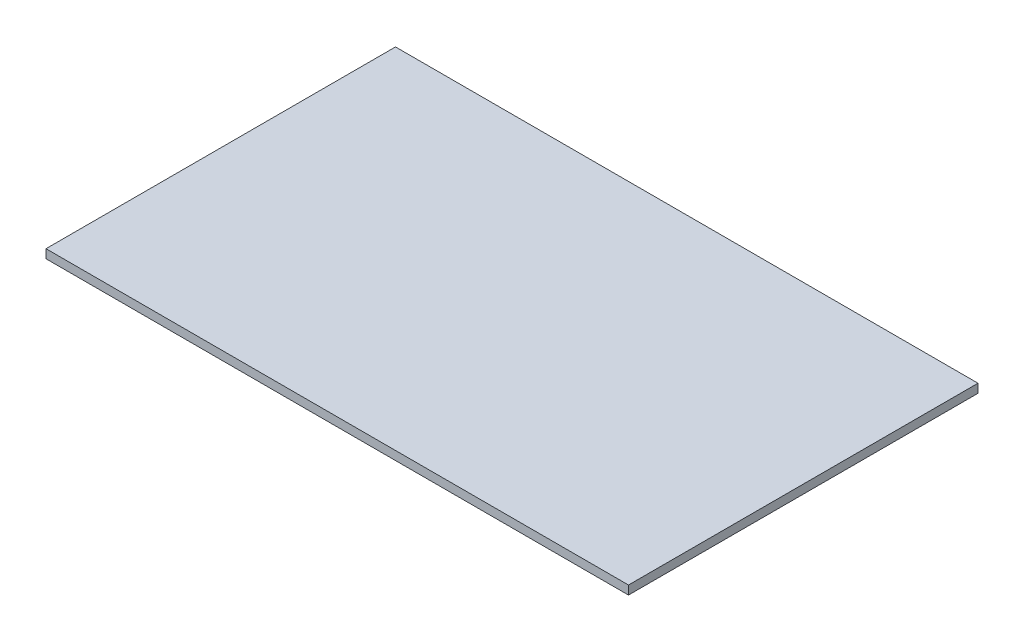
SolidWorks part; units mm, degrees
ref_plane "Front Plane" through (0, 0, 0) normal (0, 0, 1) x (1, 0, 0)
ref_plane "Top Plane" through (0, 0, 0) normal (0, 1, 0) x (1, 0, 0)
ref_plane "Right Plane" through (0, 0, 0) normal (1, 0, 0) x (0, 0, -1)
sketch "Sketch2" plane through (0, 0, 0) normal (0, 1, 0) x (1, 0, 0)
  line L1 (0, 0) -> (508, 0)
  line L2 (0, 0) -> (0, 304.8)
  line L3 (0, 304.8) -> (508, 304.8)
  line L4 (508, 0) -> (508, 304.8)
  dimension "D1" = 508
  dimension "D2" = 304.8
extrude "Boss-Extrude1" add sketch "Sketch2" along normal blind 7.62
